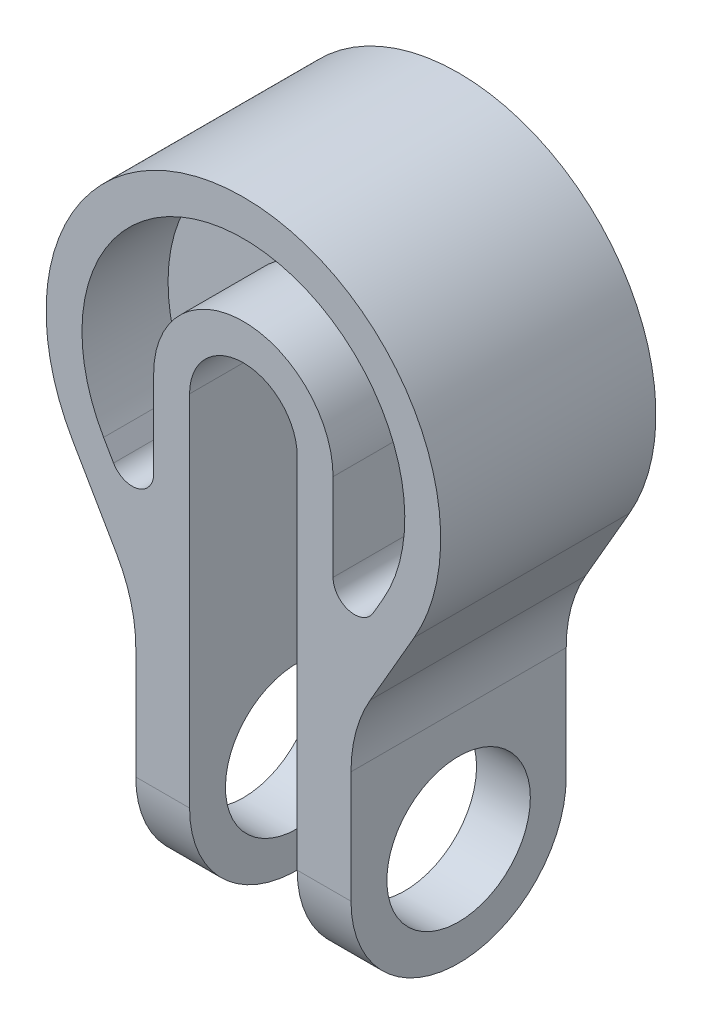
SolidWorks part; units mm, degrees
ref_plane "Front Plane" through (0, 0, 0) normal (0, 0, 1) x (1, 0, 0)
ref_plane "Top Plane" through (0, 0, 0) normal (0, 1, 0) x (1, 0, 0)
ref_plane "Right Plane" through (0, 0, 0) normal (1, 0, 0) x (0, 0, -1)
sketch "Sketch1" plane through (0, 0, 0) normal (0, 0, 1) x (1, 0, 0)
  line L0 (0, -55) -> (-33.3238, 2.7185) construction
  line L5 (0, -55) -> (36.5586, 8.3213) construction
  line L6 (0, -55) -> (0, 26.6727) construction
  line L7 (-7.5, 0) -> (-7.5, -65)
  line L8 (7.5, 0) -> (7.5, -65)
  line L9 (-15, -65) -> (-15, -42.296)
  line L10 (-15, -65) -> (-7.5, -65)
  line L11 (15, -65) -> (15, -34.3782)
  line L12 (-23.8157, -13.75) -> (-17.6795, -24.3782)
  line L13 (-15, -42.296) -> (-15, -34.3782)
  line L14 (23.8157, -13.75) -> (17.6795, -24.3782)
  line L15 (7.5, -65) -> (15, -65)
  arc A2 (23.8157, -13.75) -> (-23.8157, -13.75) centre (0, 0) ccw
  arc A3 (7.5, 0) -> (-7.5, 0) centre (0, 0) ccw
  arc A4 (15, -34.3782) -> (17.6795, -24.3782) centre (35, -34.3782) cw
  arc A5 (-15, -34.3782) -> (-17.6795, -24.3782) centre (-35, -34.3782) ccw
  point P8 (0, 0)
  point P17 (0, 0)
  point P21 (15, -29.0192)
  point P24 (-15, -29.0192)
  dimension "D1" = 30
  dimension "D2" = 30
  dimension "D6" = 15
  dimension "D3" = 55
  dimension "D4" = 15
  dimension "D7" = 20
  dimension "D5" = 30
  dimension "D8" = 65
extrude "Boss-Extrude1" add sketch "Sketch1" along normal blind 15
sketch "Sketch2" plane through (0, 0, 15) normal (0, 0, 1) x (1, 0, 0)
  line L0 (-22.5, 0) -> (22.5, 0) construction
  line L1 (0, -45) -> (-28.8277, 4.9311) construction
  line L2 (0, -45) -> (31.9993, 10.4244) construction
  line L3 (0, 0) -> (0, -45) construction
  line L4 (-12.5, 0) -> (-12.5, -12.1532)
  line L5 (12.5, 0) -> (12.5, -12.1532)
  line L6 (-19.4856, -11.25) -> (-18.0981, -13.6532)
  line L7 (19.4856, -11.25) -> (18.0981, -13.6532)
  arc A0 (19.4856, -11.25) -> (-19.4856, -11.25) centre (0, 0) ccw
  arc A1 (23.8157, -13.75) -> (-23.8157, -13.75) centre (0, 0) ccw construction
  arc A2 (12.5, 0) -> (-12.5, 0) centre (0, 0) ccw
  arc A3 (7.5, 0) -> (-7.5, 0) centre (0, 0) ccw construction
  arc A4 (12.5, -12.1532) -> (18.0981, -13.6532) centre (15.5, -12.1532) ccw
  arc A5 (-12.5, -12.1532) -> (-18.0981, -13.6532) centre (-15.5, -12.1532) cw
  point P12 (0, 0)
  point P22 (12.5, -23.3494)
  point P25 (-12.5, -23.3494)
  dimension "D1" = 5
  dimension "D4" = 5
  dimension "D5" = 3
  dimension "D2" = 30
  dimension "D3" = 30
extrude "Cut-Extrude1" cut sketch "Sketch2" against normal blind 12
mirror "Mirror1" about plane through (0, 0, 0) normal (0, 0, 1) of bodies 102
sketch "Sketch3" plane through (15, 0, 0) normal (1, 0, 0) x (0, 0, -1)
  line L0 (-15, -65) -> (-15, -34.3782) construction
  line L1 (15, -65) -> (15, -34.3782) construction
  line L2 (-15, -65) -> (15, -65) construction
  line L3 (0, -50) -> (0, 0) construction
  circle A0 centre (0, -50) radius 15
  circle A1 centre (0, -50) radius 10
  dimension "D1" = 5
extrude "Cut-Extrude2" cut sketch "Sketch3" against normal up to next
mirror "Mirror2" about plane through (0, 0, 0) normal (1, 0, 0) of "Cut-Extrude2"
